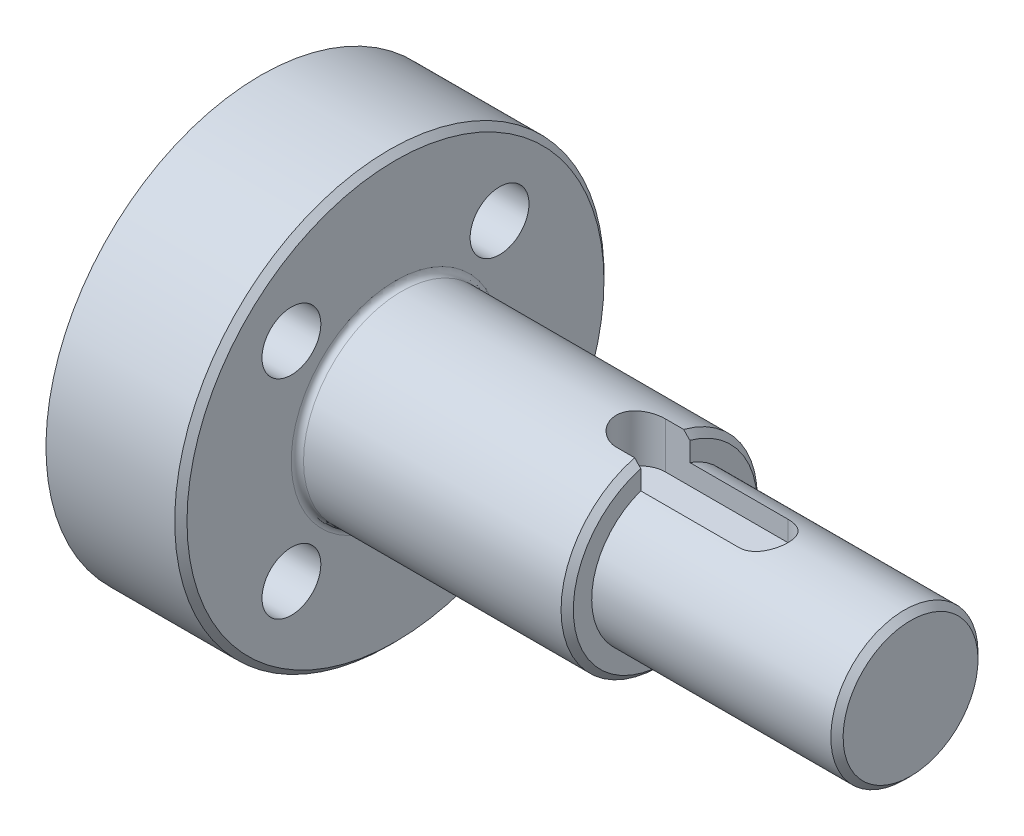
SolidWorks part; units mm, degrees
material "6061-T6 "
ref_plane "Front Plane" through (0, 0, 0) normal (0, 0, 1) x (1, 0, 0)
ref_plane "Top Plane" through (0, 0, 0) normal (0, 1, 0) x (1, 0, 0)
ref_plane "Right Plane" through (0, 0, 0) normal (1, 0, 0) x (0, 0, -1)
sketch "Sketch1" plane through (0, 0, 0) normal (0, 0, 1) x (1, 0, 0)
  line L0 (0, 0) -> (0, 8)
  line L1 (-0.75, 8) -> (-2.5, 8)
  line L2 (-2.5, 8) -> (-2.5, 8.75)
  line L3 (-2.5, 8.75) -> (3, 8.75)
  line L4 (3, 8.75) -> (3, 4)
  line L5 (3, 4) -> (14, 4)
  line L6 (14, 4) -> (14, 3)
  line L7 (14, 3) -> (24, 3)
  line L8 (24, 3) -> (24, 0)
  line L9 (24, 0) -> (0, 0)
  line L11 (6, 4) -> (6, 6) construction
  line L12 (6, 6) -> (9.5, 6) construction
  line L13 (9.5, 6) -> (9.5, 4) construction
  line L14 (14, 4) -> (14, 6.8) construction
  line L15 (14, 6.8) -> (18, 6.8) construction
  line L16 (18, 6.8) -> (18, 3) construction
  line L17 (9.5, 6) -> (11.5, 6) construction
  line L18 (11.5, 6) -> (11.5, 8) construction
  line L19 (0, 0) -> (-3, 0) construction
  line L20 (-3, 0) -> (-3, 8) construction
  line L21 (-3, 8) -> (-2.7343, 8) construction
  line L22 (19, 3) -> (19, 5) construction
  line L23 (19, 5) -> (22, 5) construction
  line L24 (22, 5) -> (22, 3) construction
  line L25 (-0.375, 8.2165) -> (-0.75, 8)
  arc A0 (0, 8) -> (-0.375, 8.2165) centre (-0.25, 8) ccw
  dimension "D22" = 0.5
  dimension "D1" = 8
  dimension "D2" = 2.5
  dimension "D3" = 0.75
  dimension "D4" = 3
  dimension "D5" = 4
  dimension "D7" = 3
  dimension "D8" = 3.5
  dimension "D9" = 6
  dimension "D10" = 3
  dimension "D11" = 2
  dimension "D12" = 4
  dimension "D13" = 6.8
  dimension "D14" = 2.5
  dimension "D15" = 3
  dimension "D16" = 3
  dimension "D17" = 1
  dimension "D18" = 5
  dimension "D19" = 2
  dimension "D21" = 30
revolve "Revolve1" add sketch "Sketch1" angle 360 about L9
hole_wizard "M2 Clearance Hole2" positions "Sketch3" profile "Sketch4" hole size "M2" standard "ANSI Metric" end condition through all
sketch "Sketch3" plane through (3, 0, 0) normal (1, 0, 0) x (0, 0, -1)
  line L0 (-4.2426, 4.2426) -> (4.2426, -4.2426) construction
  line L2 (4.2426, 4.2426) -> (-4.2426, -4.2426) construction
  line L4 (0, 0) -> (0, 6) construction
  circle A0 centre (0, 0) radius 6 construction
  circle A1 centre (-4.2426, 4.2426) radius 1.75 construction
  point P6 (-4.2426, 4.2426)
  point P7 (4.2426, -4.2426)
  point P9 (4.2426, 4.2426)
  point P10 (-4.2426, -4.2426)
  point P25 (-4.2426, 4.2426)
  point P27 (-4.2426, -4.2426)
  point P29 (4.2426, -4.2426)
  point P31 (4.2426, 4.2426)
  dimension "D1" = 12
  dimension "D3" = 3.5
  dimension "D2" = 45
sketch "Sketch4" plane through (3, 4.2426, -4.2426) normal (0, 1, 0) x (0, 0, -1)
  line L0 (0, 0) -> (0, 5.5)
  line L1 (0, 5.5) -> (1.2, 5.5)
  line L2 (1.2, 5.5) -> (1.2, 0)
  line L5 (1.2, 0) -> (0, 0)
  line L11 (0, -6.35) -> (0, 107.95) construction
  dimension "Thru Hole Dia." = 2.4
  dimension "Thru Hole Depth" = 5.5
chamfer "Chamfer2" distance 0.25 angle 45 3 edges at (14, 4, 0) (24, 3, 0) (3, 8.75, 0)
sketch "Sketch5" plane through (0, 0, 0) normal (0, 1, 0) x (1, 0, 0)
  line L0 (14, -3) -> (14, 3) construction
  line L1 (13, 0) -> (18, 0) construction
  line L9 (13, 1) -> (18, 1)
  line L10 (13, -1) -> (18, -1)
  arc A6 (13, 1) -> (13, -1) centre (13, 0) ccw
  arc A7 (18, -1) -> (18, 1) centre (18, 0) ccw
  point P4 (15.5, 0)
  dimension "D3" = 1
  dimension "D1" = 5
  dimension "D2" = 2
extrude "Cut-Extrude1" cut sketch "Sketch5" along normal through all from offset 2
fillet "Fillet1" radius 0.25 1 edges at (3, 4, 0)
